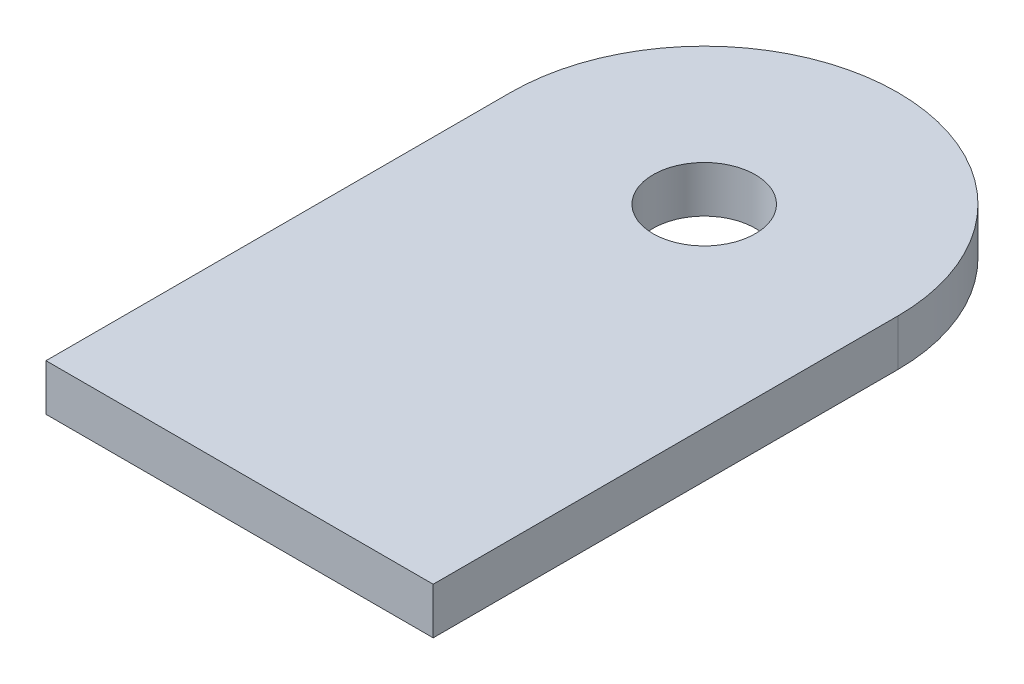
SolidWorks part; units mm, degrees
ref_plane "Front Plane" through (0, 0, 0) normal (0, 0, 1) x (1, 0, 0)
ref_plane "Top Plane" through (0, 0, 0) normal (0, 1, 0) x (1, 0, 0)
ref_plane "Right Plane" through (0, 0, 0) normal (1, 0, 0) x (0, 0, -1)
sketch "Sketch1" plane through (0, 0, 0) normal (0, 1, 0) x (1, 0, 0)
  line L0 (-22.78, 39.7975) -> (-22.78, 9.7975)
  line L1 (2.22, 39.7975) -> (2.22, 9.7975)
  line L2 (-22.78, 9.7975) -> (2.22, 9.7975)
  circle A1 centre (-10.28, 39.7975) radius 12.5
  circle A2 centre (-10.28, 39.7975) radius 3.302
  dimension "D1" = 6.604
  dimension "D2" = 25
  dimension "D3" = 30
extrude "Boss-Extrude1" add sketch "Sketch1" along normal blind 3
